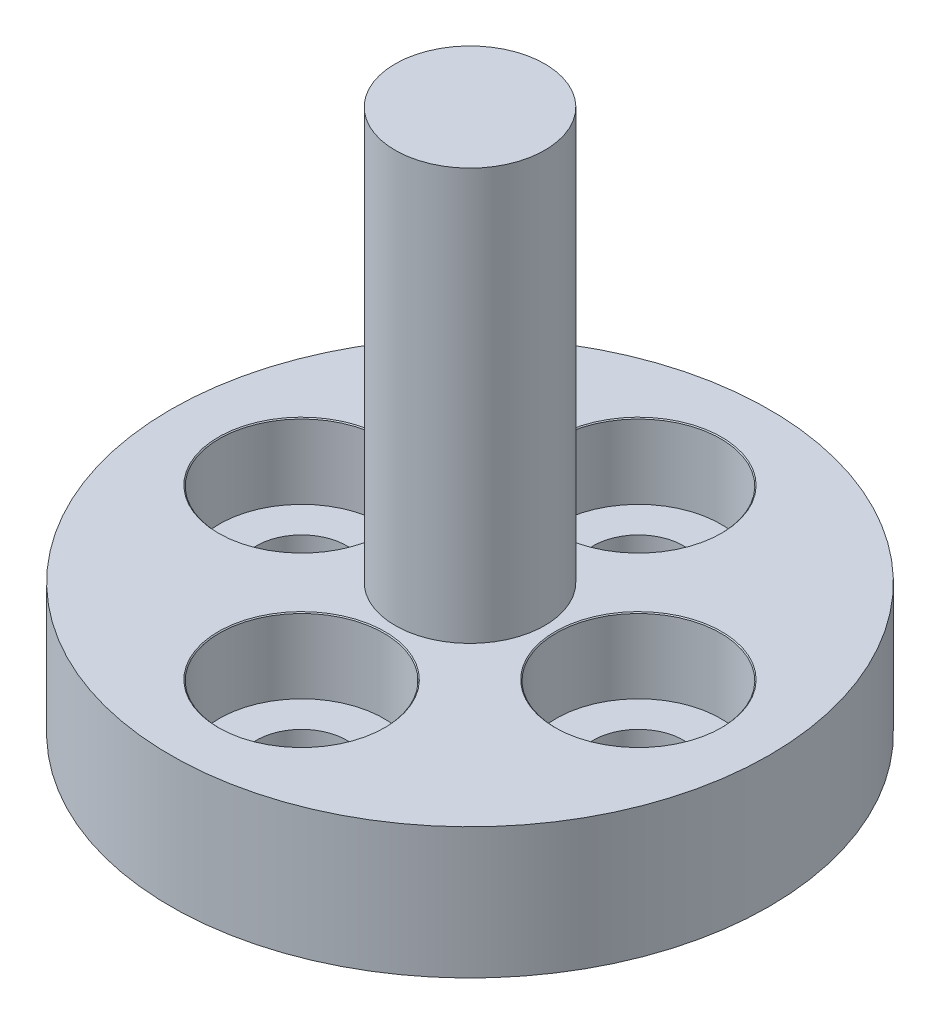
SolidWorks part; units mm, degrees
ref_plane "Front Plane" through (0, 0, 0) normal (0, 0, 1) x (1, 0, 0)
ref_plane "Top Plane" through (0, 0, 0) normal (0, 1, 0) x (1, 0, 0)
ref_plane "Right Plane" through (0, 0, 0) normal (1, 0, 0) x (0, 0, -1)
sketch "Sketch1" plane through (0, 0, 0) normal (0, 0, 1) x (1, 0, 0)
  line L0 (0, 0) -> (8, 0)
  line L1 (8, 0) -> (8, 3.5)
  line L2 (8, 3.5) -> (2, 3.5)
  line L3 (2, 3.5) -> (2, 14.5)
  line L4 (2, 14.5) -> (0, 14.5)
  line L5 (0, 14.5) -> (0, 0)
  dimension "D1" = 8
  dimension "D2" = 14.5
  dimension "D3" = 11
  dimension "D4" = 2
revolve "Revolve1" add sketch "Sketch1" angle 360 about L5
sketch "Sketch2" plane through (0, 3.5, 0) normal (0, 1, 0) x (1, 0, 0)
  circle A0 centre (0, 0) radius 4.5
  dimension "D1" = 9
hole_wizard "CBORE for M2 SHCS1" positions "Sketch5" profile "Sketch4" counterbore size "M2" standard "ANSI Metric" end condition through all
sketch "Sketch5" plane through (0, 3.5, 0) normal (0, 1, 0) x (1, 0, 0)
  circle A0 centre (0, 0) radius 4.5 construction
  point P0 (-4.5, 0)
  point P4 (0, 4.5)
  point P6 (4.5, 0)
  point P8 (0, -4.5)
sketch "Sketch4" plane through (-4.5, 3.5, 0) normal (1, 0, 0) x (0, 0, 1)
  line L0 (0, 0) -> (0, 3.5)
  line L1 (0, 3.5) -> (1.2, 3.5)
  line L3 (1.2, 3.5) -> (1.2, 2)
  line L4 (2.2, 2) -> (1.2, 2)
  line L5 (2.2, 2) -> (2.2, 0.025)
  line L6 (2.2, 0.025) -> (2.225, 0)
  line L7 (2.225, 0) -> (0, 0)
  line L8 (-2.2, 0.025) -> (-2.225, 0) construction
  line L11 (0, -6.35) -> (0, 107.95) construction
  dimension "Thru Hole Dia." = 2.4
  dimension "Thru Hole Depth" = 3.5
  dimension "C'Bore Dia." = 4.4
  dimension "C'Bore Depth" = 2
  dimension "Near C'Sink Dia." = 4.45
  dimension "Near C'Sink Angle" = 90
